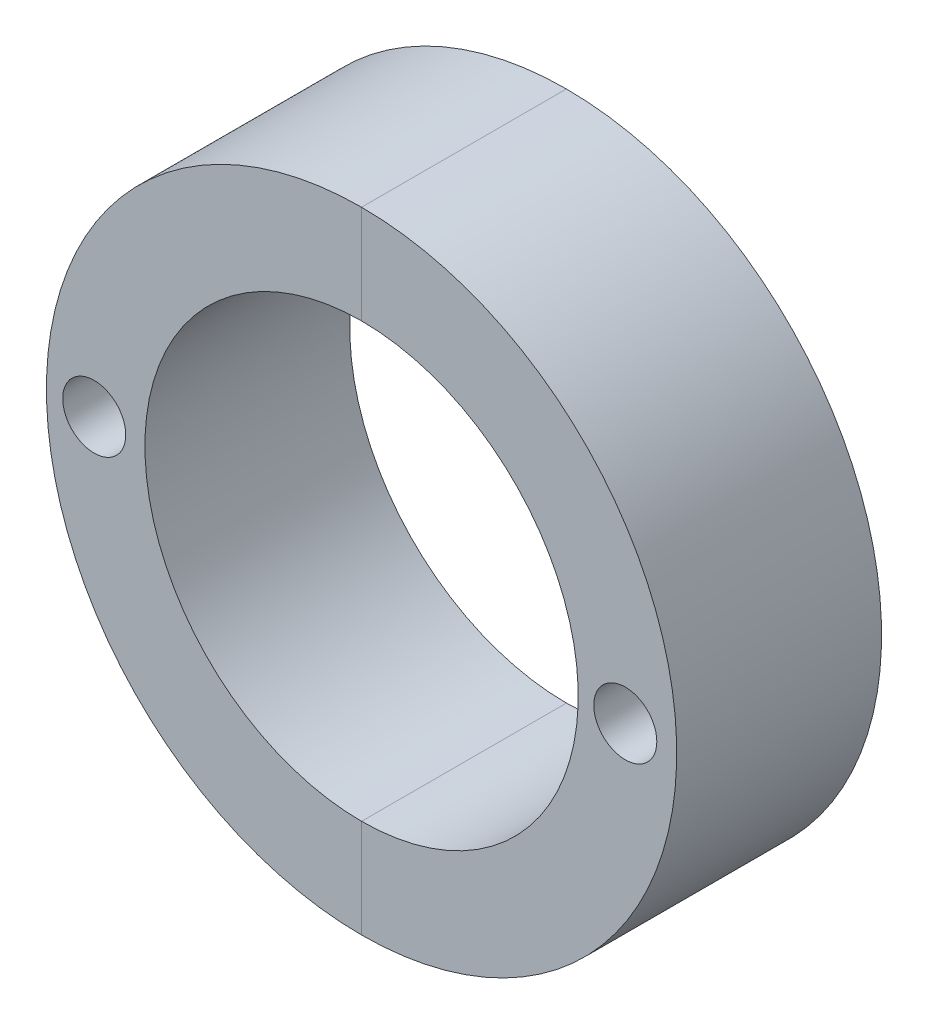
SolidWorks part; units mm, degrees
material "Plain Carbon Steel"
ref_plane "Front Plane" through (0, 0, 0) normal (0, 0, 1) x (1, 0, 0)
ref_plane "Top Plane" through (0, 0, 0) normal (0, 1, 0) x (1, 0, 0)
ref_plane "Right Plane" through (0, 0, 0) normal (1, 0, 0) x (0, 0, -1)
sketch "Sketch1" plane through (0, 0, 0) normal (0, 0, 1) x (1, 0, 0)
  circle A0 centre (0, 0) radius 40
  dimension "D1" = 80
extrude "Boss-Extrude1" add sketch "Sketch1" along normal blind 26 contours A0
sketch "Sketch2" plane through (0, 0, 26) normal (0, 0, 1) x (1, 0, 0)
  circle A0 centre (0, 0) radius 27.5
  dimension "D1" = 55
extrude "Cut-Extrude1" cut sketch "Sketch2" against normal through all contours A0
sketch "Sketch3" plane through (0, 0, 0) normal (0, 0, 1) x (1, 0, 0)
  line L0 (0, 44.4068) -> (0, -43.8585)
split "Split1" trim tools "Sketch3" bodies to split 103 resulting bodies 104 105
sketch "Sketch4" plane through (0, 0, 26) normal (0, 0, 1) x (1, 0, 0)
  circle A0 centre (-33.9317, 0) radius 4
  circle A1 centre (33.472, 0) radius 4
  dimension "D1" = 8
  dimension "D2" = 8
extrude "Cut-Extrude3" cut sketch "Sketch4" against normal through all contours A1 | A0
